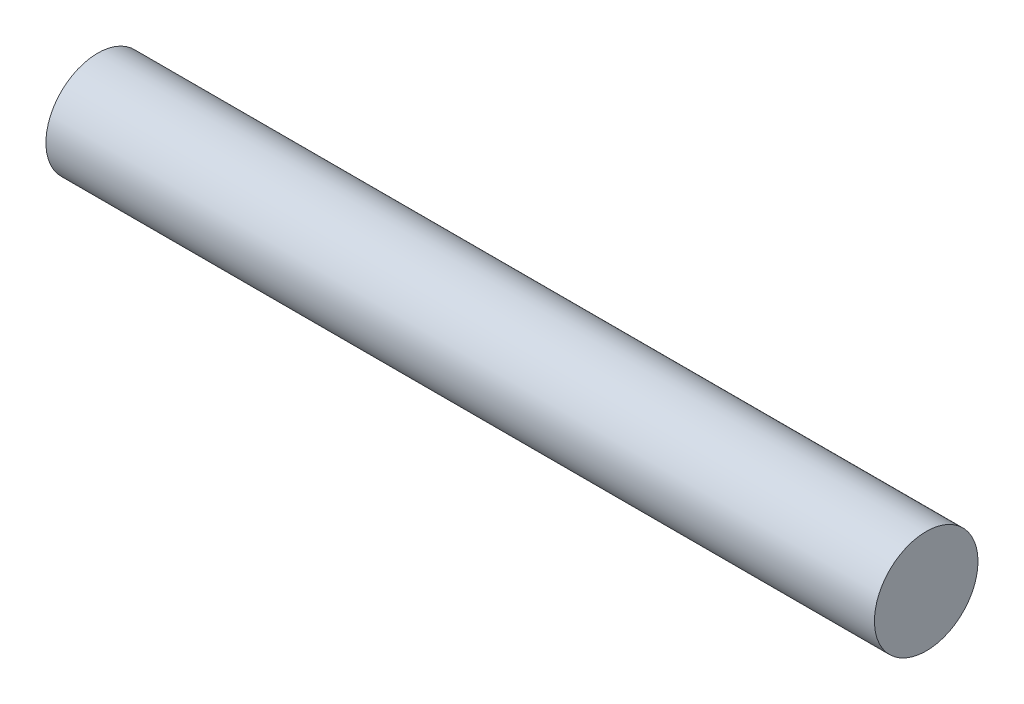
SolidWorks part; units mm, degrees
material "PETG"
ref_plane "Front Plane" through (0, 0, 0) normal (0, 0, 1) x (1, 0, 0)
ref_plane "Top Plane" through (0, 0, 0) normal (0, 1, 0) x (1, 0, 0)
ref_plane "Right Plane" through (0, 0, 0) normal (1, 0, 0) x (0, 0, -1)
sketch "Sketch1" plane through (0, 0, 0) normal (1, 0, 0) x (0, 0, -1)
  circle A0 centre (0, 0) radius 1
  dimension "D1" = 2
extrude "Boss-Extrude1" add sketch "Sketch1" along normal blind 16
ref_plane "Plane1" through (8, 0, 0) normal (1, 0, 0) x (0, 0, -1)
scale "Scale1" scale about origin uniform scaling yes scale factor 1
